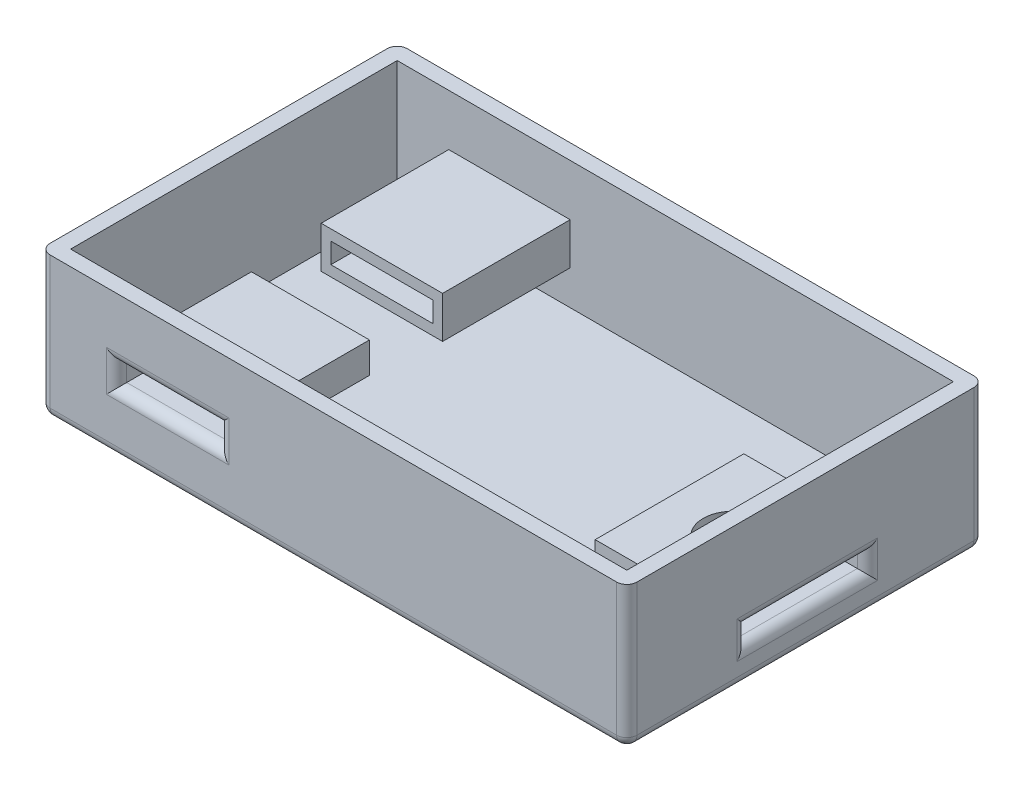
SolidWorks part; units mm, degrees
ref_plane "Front Plane" through (0, 0, 0) normal (0, 0, 1) x (1, 0, 0)
ref_plane "Top Plane" through (0, 0, 0) normal (0, 1, 0) x (1, 0, 0)
ref_plane "Right Plane" through (0, 0, 0) normal (1, 0, 0) x (0, 0, -1)
sketch "Sketch1" plane through (0, 0, 0) normal (0, 1, 0) x (1, 0, 0)
  line L1 (-57.5, 35) -> (57.5, 35)
  line L2 (-57.5, 35) -> (-57.5, -35)
  line L3 (-57.5, -35) -> (57.5, -35)
  line L4 (57.5, 35) -> (57.5, -35)
  line L5 (-57.5, 35) -> (57.5, -35) construction
  line L6 (-57.5, -35) -> (57.5, 35) construction
  point P0 (0, 0)
  dimension "D1" = 115
  dimension "D2" = 70
extrude "Boss-Extrude1" add sketch "Sketch1" along normal blind 28
sketch "Sketch2" plane through (0, 0, 35) normal (0, 0, 1) x (1, 0, 0)
  line L1 (-57.5, 28) -> (-57.5, 0) construction
  line L4 (-42.5, 15.8543) -> (-22.5, 15.8543)
  line L5 (-42.5, 15.8543) -> (-42.5, 11.8543)
  line L6 (-42.5, 11.8543) -> (-22.5, 11.8543)
  line L7 (-22.5, 15.8543) -> (-22.5, 11.8543)
  line L8 (-42.5, 15.8543) -> (-22.5, 11.8543) construction
  line L9 (-42.5, 11.8543) -> (-22.5, 15.8543) construction
  point P10 (-32.5, 13.8543)
  dimension "D1" = 15
  dimension "D2" = 20
  dimension "D3" = 4
shell "Shell2" thickness 3
extrude "Cut-Extrude1" cut sketch "Sketch2" against normal through all
sketch "Sketch4" plane through (0, 0, -32) normal (0, 0, 1) x (1, 0, 0)
  line L1 (-42.5, 15.8543) -> (-22.5, 15.8543)
  line L2 (-42.5, 15.8543) -> (-42.5, 11.8543)
  line L3 (-42.5, 11.8543) -> (-22.5, 11.8543)
  line L4 (-22.5, 15.8543) -> (-22.5, 11.8543)
  line L7 (-44.3984, 17.937) -> (-20.6016, 17.937)
  line L8 (-44.3984, 17.937) -> (-44.3984, 9.7715)
  line L9 (-44.3984, 9.7715) -> (-20.6016, 9.7715)
  line L10 (-20.6016, 17.937) -> (-20.6016, 9.7715)
  point P4 (-32.5, 13.8543)
  point P7 (-32.5, 13.8543)
extrude "Boss-Extrude2" add sketch "Sketch4" along normal blind 25
sketch "Sketch5" plane through (0, 0, 32) normal (0, 0, -1) x (-1, 0, 0)
  line L1 (22.5, 15.8543) -> (42.5, 15.8543)
  line L2 (22.5, 15.8543) -> (22.5, 11.8543)
  line L3 (22.5, 11.8543) -> (42.5, 11.8543)
  line L4 (42.5, 15.8543) -> (42.5, 11.8543)
  line L7 (20.9374, 16.8632) -> (44.0626, 16.8632)
  line L8 (20.9374, 16.8632) -> (20.9374, 10.8454)
  line L9 (20.9374, 10.8454) -> (44.0626, 10.8454)
  line L10 (44.0626, 16.8632) -> (44.0626, 10.8454)
  point P4 (32.5, 13.8543)
  point P7 (32.5, 13.8543)
extrude "Boss-Extrude3" add sketch "Sketch5" along normal blind 25
fillet "Fillet2" radius 2 8 edges at (57.5, 14, -35) (57.5, 0, 0) (57.5, 14, 35) (-57.5, 14, -35) (0, 0, -35) (0, 0, 35) (-57.5, 14, 35) (-57.5, 0, 0)
fillet "Fillet3" radius 2 8 edges at (-42.5, 13.8543, 35) (-32.5, 11.8543, 35) (-22.5, 13.8543, 35) (-32.5, 15.8543, 35) (-32.5, 11.8543, -35) (-42.5, 13.8543, -35) (-22.5, 13.8543, -35) (-32.5, 15.8543, -35)
sketch "Sketch9" plane through (57.5, 0, 0) normal (-1, 0, 0) x (0, 0, 1)
  line L1 (-14.937, 12.289) -> (14.1993, 12.289)
  line L2 (-14.937, 12.289) -> (-14.937, 4.3278)
  line L3 (-14.937, 4.3278) -> (14.1993, 4.3278)
  line L4 (14.1993, 12.289) -> (14.1993, 4.3278)
  line L5 (-14.937, 12.289) -> (14.1993, 4.3278) construction
  line L6 (-14.937, 4.3278) -> (14.1993, 12.289) construction
  point P0 (-0.3688, 8.3084)
extrude "Boss-Extrude4" add sketch "Sketch9" along normal blind 25
sketch "Sketch11" plane through (32.5, 0, 0) normal (-1, 0, 0) x (0, 0, 1)
  line L0 (-0.3688, 12.289) -> (-0.3688, 4.3278) construction
  line L1 (14.1993, 12.289) -> (-14.937, 12.289) construction
  line L2 (-14.937, 4.3278) -> (14.1993, 4.3278) construction
  line L3 (-14.937, 8.3084) -> (14.1993, 8.3084) construction
  line L4 (-14.937, 12.289) -> (-14.937, 4.3278) construction
  line L5 (14.1993, 4.3278) -> (14.1993, 12.289) construction
  line L7 (-12.176, 9.922) -> (11.4383, 9.922)
  line L8 (-12.176, 9.922) -> (-12.176, 6.6948)
  line L9 (-12.176, 6.6948) -> (11.4383, 6.6948)
  line L10 (11.4383, 9.922) -> (11.4383, 6.6948)
  line L11 (-12.176, 9.922) -> (11.4383, 6.6948) construction
  line L12 (-12.176, 6.6948) -> (11.4383, 9.922) construction
  point P12 (-0.3688, 8.3084)
extrude "Cut-Extrude4" cut sketch "Sketch11" against normal through all
fillet "Fillet4" radius 2 4 edges at (57.5, 8.3084, -12.176) (57.5, 9.922, -0.3688) (57.5, 8.3084, 11.4383) (57.5, 6.6948, -0.3688)
sketch "Sketch12" plane through (0, 12.289, 0) normal (0, 1, 0) x (1, 0, 0)
  circle A0 centre (43.3551, 0) radius 5.8846
extrude "Cut-Extrude5" cut sketch "Sketch12" against normal up to next
sketch "Sketch13" plane through (32.5, 0, 0) normal (-1, 0, 0) x (0, 0, 1)
  line L1 (-14.937, 12.289) -> (14.1993, 12.289)
  line L2 (-14.937, 12.289) -> (-14.937, 4.3278)
  line L3 (-14.937, 4.3278) -> (14.1993, 4.3278)
  line L4 (14.1993, 12.289) -> (14.1993, 4.3278)
  line L5 (-14.937, 12.289) -> (14.1993, 4.3278) construction
  line L6 (-14.937, 4.3278) -> (14.1993, 12.289) construction
  point P5 (-0.3688, 8.3084)
extrude "Boss-Extrude5" add sketch "Sketch13" along normal blind 2
